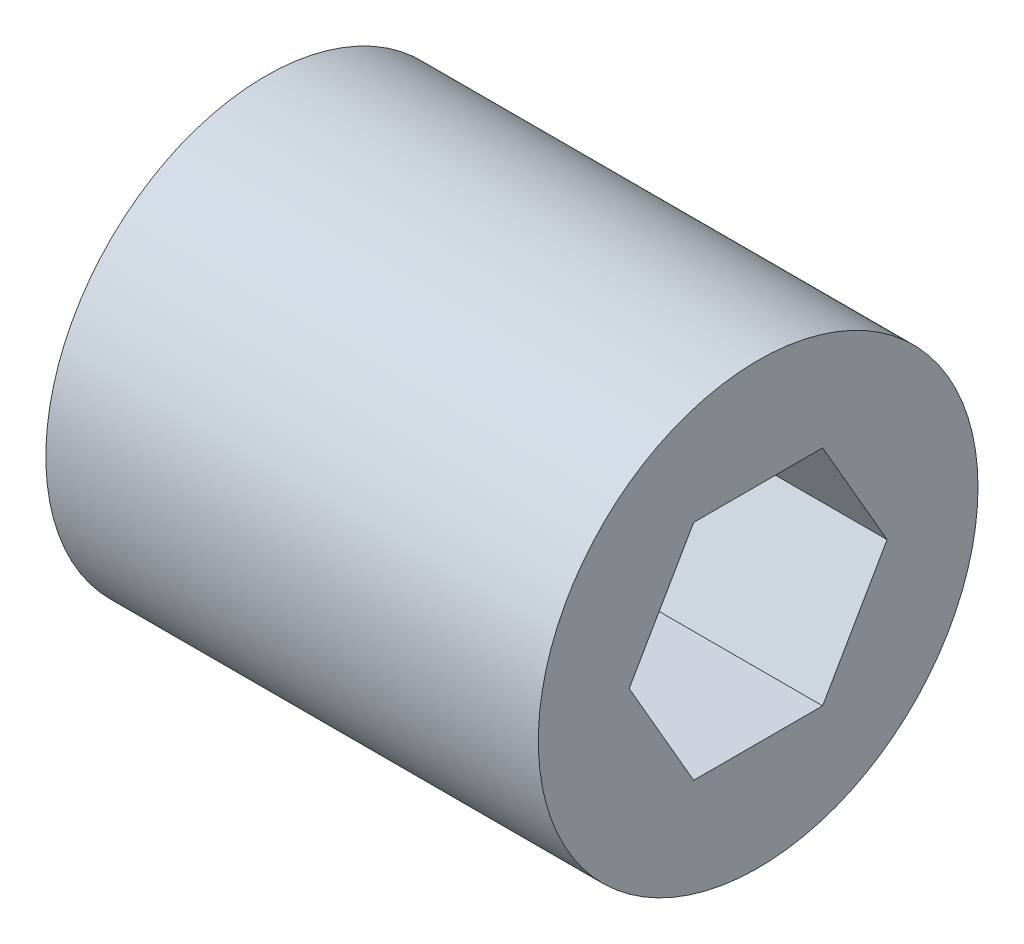
SolidWorks part; units mm, degrees
ref_plane "Alzado" through (0, 0, 0) normal (0, 0, 1) x (1, 0, 0)
ref_plane "Planta" through (0, 0, 0) normal (0, 1, 0) x (1, 0, 0)
ref_plane "Vista lateral" through (0, 0, 0) normal (1, 0, 0) x (0, 0, -1)
sketch "Croquis1" plane through (0, 0, 0) normal (1, 0, 0) x (0, 0, -1)
  line L1 (7.3323, 0) -> (3.6662, 6.35)
  line L2 (3.6662, 6.35) -> (-3.6662, 6.35)
  line L3 (-3.6662, 6.35) -> (-7.3323, 0)
  line L4 (-7.3323, 0) -> (-3.6662, -6.35)
  line L5 (-3.6662, -6.35) -> (3.6662, -6.35)
  line L6 (3.6662, -6.35) -> (7.3323, 0)
  circle A0 centre (0, 0) radius 12.5
  circle A1 centre (0, 0) radius 6.35 construction
  dimension "D1" = 25
  dimension "D2" = 12.7
extrude "Saliente-Extruir1" add sketch "Croquis1" along normal blind 28
